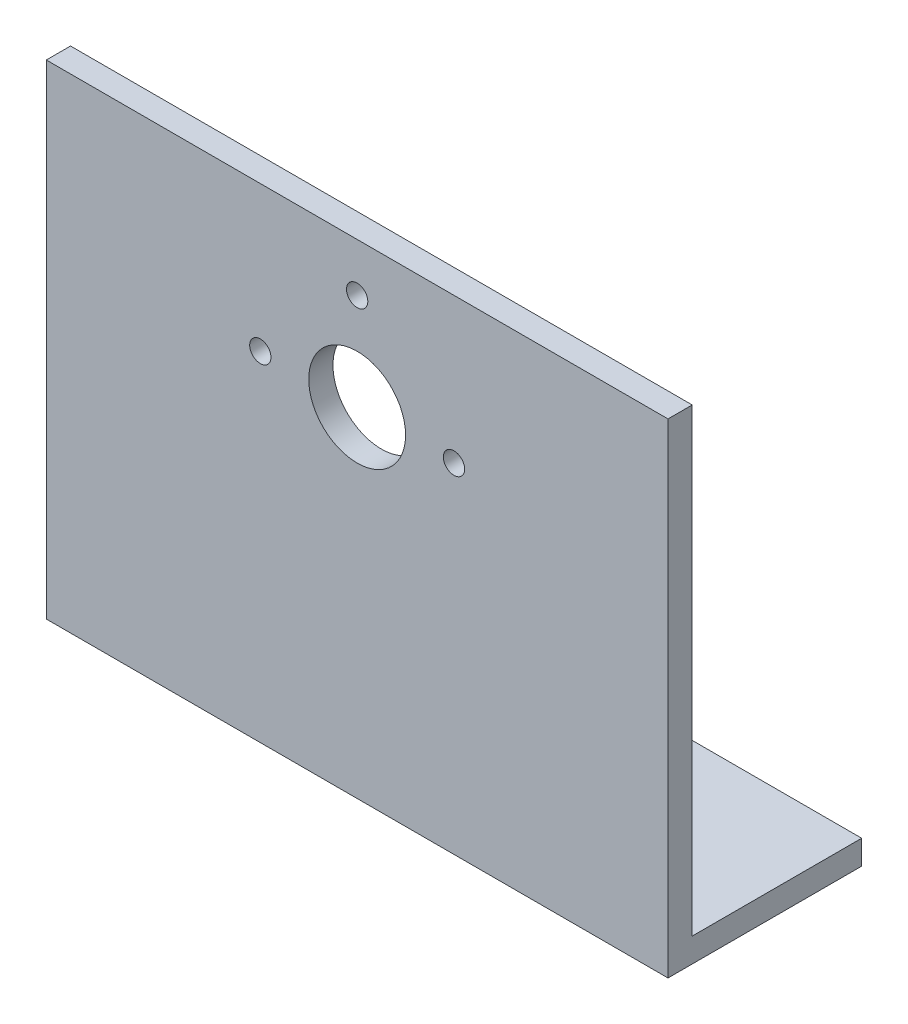
SolidWorks part; units mm, degrees
ref_plane "Front Plane" through (0, 0, 0) normal (0, 0, 1) x (1, 0, 0)
ref_plane "Top Plane" through (0, 0, 0) normal (0, 1, 0) x (1, 0, 0)
ref_plane "Right Plane" through (0, 0, 0) normal (1, 0, 0) x (0, 0, -1)
sketch "Sketch1" plane through (0, 0, 0) normal (0, 0, 1) x (1, 0, 0)
  line L1 (40.7658, 19.05) -> (-40.7658, 19.05)
  line L2 (40.7658, 19.05) -> (40.7658, -44.45)
  line L3 (40.7658, -44.45) -> (-40.7658, -44.45)
  line L4 (-40.7658, 19.05) -> (-40.7658, -44.45)
  circle A0 centre (0, 0) radius 6.35
  circle A1 centre (0, 12.7) radius 1.397
  circle A2 centre (-12.7, 0) radius 1.397
  circle A3 centre (12.7, 0) radius 1.397
  point P0 (0, 0)
extrude "Boss-Extrude1" add sketch "Sketch1" along normal blind 3.175
sketch "Sketch2" plane through (0, 0, 0) normal (0, 0, -1) x (-1, 0, 0)
  line L0 (40.7658, 19.05) -> (40.7658, -44.45) construction
  line L1 (-40.7658, -44.45) -> (40.7658, -44.45)
  line L2 (-40.7658, -44.45) -> (-40.7658, -41.275)
  line L3 (-40.7658, -41.275) -> (40.7658, -41.275)
  line L4 (40.7658, -44.45) -> (40.7658, -41.275)
extrude "Boss-Extrude2" add sketch "Sketch2" along normal blind 22.225
sketch "Sketch3" plane through (0, -41.275, 0) normal (0, 1, 0) x (1, 0, 0)
  circle A0 centre (-19.05, 17.78) radius 1.397
  circle A1 centre (19.05, 17.78) radius 1.397
extrude "Cut-Extrude1" cut sketch "Sketch3" against normal blind 3175
